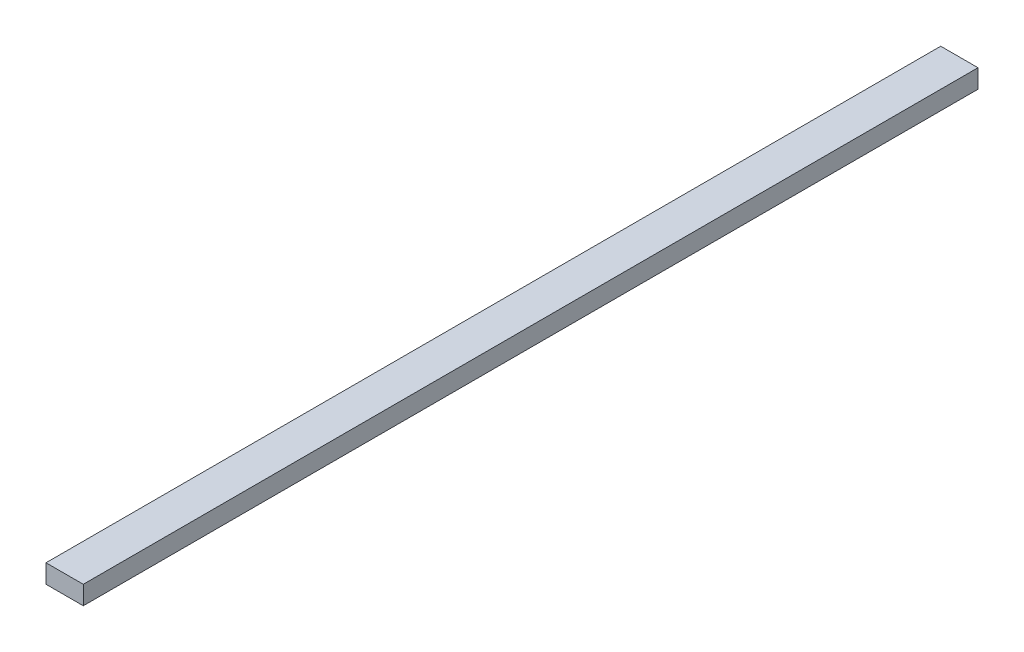
SolidWorks part; units mm, degrees
ref_plane "Front Plane" through (0, 0, 0) normal (0, 0, 1) x (1, 0, 0)
ref_plane "Top Plane" through (0, 0, 0) normal (0, 1, 0) x (1, 0, 0)
ref_plane "Right Plane" through (0, 0, 0) normal (1, 0, 0) x (0, 0, -1)
sketch "Sketch1" plane through (0, 0, 0) normal (0, 0, 1) x (1, 0, 0)
  line L1 (-25.4, -12.7) -> (25.4, -12.7)
  line L2 (-25.4, -12.7) -> (-25.4, 12.7)
  line L3 (-25.4, 12.7) -> (25.4, 12.7)
  line L4 (25.4, -12.7) -> (25.4, 12.7)
  line L5 (-25.4, -12.7) -> (25.4, 12.7) construction
  line L6 (-25.4, 12.7) -> (25.4, -12.7) construction
  point P0 (0, 0)
  dimension "D1" = 50.8
  dimension "D2" = 25.4
extrude "Boss-Extrude3" add sketch "Sketch1" along normal blind 1219.2
